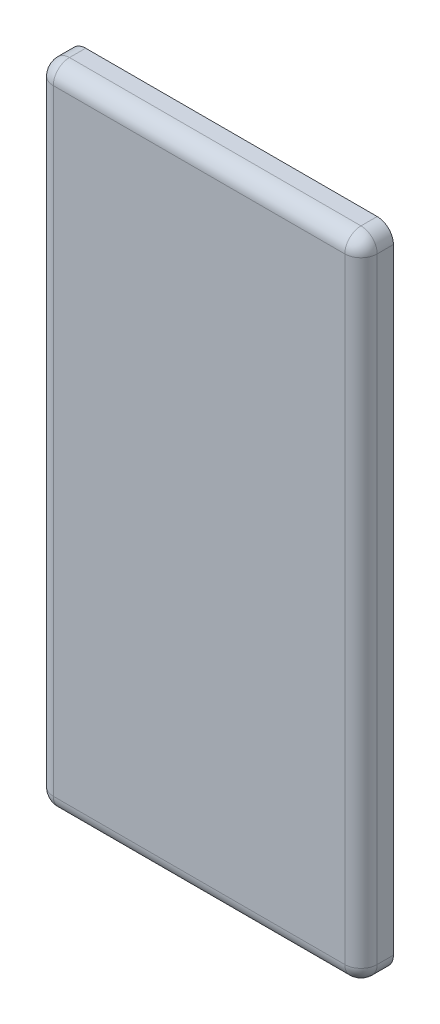
SolidWorks part; units mm, degrees
ref_plane "Top" through (0, 0, 0) normal (0, 0, 1) x (1, 0, 0)
ref_plane "Front" through (0, 0, 0) normal (0, 1, 0) x (1, 0, 0)
ref_plane "Right" through (0, 0, 0) normal (1, 0, 0) x (0, 0, -1)
sketch "Cap Sketch" plane through (0, 0, 0) normal (0, 0, 1) x (1, 0, 0)
  line L1 (-10, -20) -> (10, -20)
  line L2 (-10, -20) -> (-10, 20)
  line L3 (-10, 20) -> (10, 20)
  line L4 (10, -20) -> (10, 20)
  line L5 (-10, -20) -> (10, 20) construction
  line L6 (-10, 20) -> (10, -20) construction
  point P0 (0, 0)
  dimension "Width" = 20
  dimension "Length" = 40
extrude "Extrude Thickness" add sketch "Cap Sketch" along normal blind 2
fillet "Corner Fillets" radius 1 4 edges at (-10, -20, 1) (-10, 20, 1) (10, 20, 1) (10, -20, 1)
fillet "Top Edge Fillet" radius 1 8 edges at (-9.7071, 19.7071, 2) (0, 20, 2) (9.7071, 19.7071, 2) (10, 0, 2) (9.7071, -19.7071, 2) (0, -20, 2) (-9.7071, -19.7071, 2) (-10, 0, 2)
equation "\"M2 Close Fit Hole\"= 2.2"
equation "\"M2.5 Close Fit Hole\"= 2.7"
equation "\"M3 Close Fit Hole\"= 3.2"
equation "\"M4 Close Fit Hole\"= 4.3"
equation "\"M5 Close Fit Hole\"= 5.3"
equation "\"M6 Close Fit Hole\"= 6.3"
equation "\"M7 Close Fit Hole\"= 7.4"
equation "\"M8 Close Fit Hole\"= 8.4"
equation "\"M2 Tap Hole 75%\"= 1.6"
equation "\"M3 Tap Hole 75%\"= 2.5"
equation "\"M4 Tap Hole 75%\"= 3.3"
equation "\"M5 Tap Hole 75%\"= 4.2"
equation "\"M6 Tap Hole 75%\"= 5"
equation "\"M7 Tap Hole 75%\"= 6"
equation "\"M8 Tap Hole 75%\"= 6.8"
